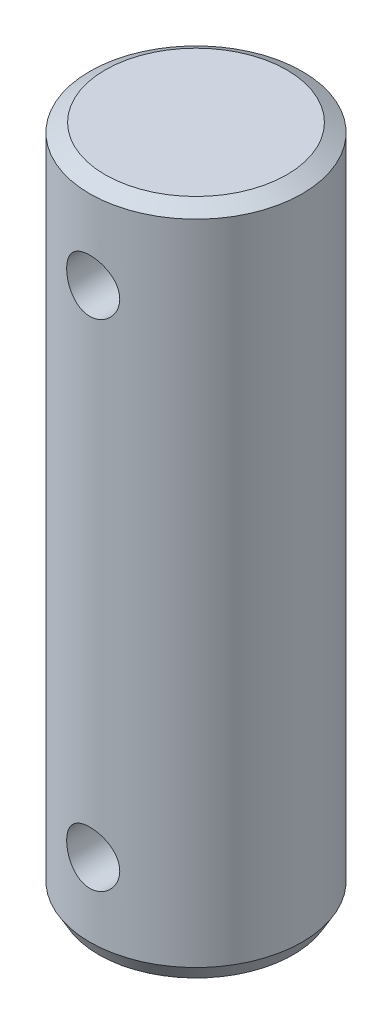
SolidWorks part; units mm, degrees
ref_plane "Front Plane" through (0, 0, 0) normal (0, 0, 1) x (1, 0, 0)
ref_plane "Top Plane" through (0, 0, 0) normal (0, 1, 0) x (1, 0, 0)
ref_plane "Right Plane" through (0, 0, 0) normal (1, 0, 0) x (0, 0, -1)
sketch "Sketch1" plane through (0, 0, 0) normal (0, 1, 0) x (1, 0, 0)
  circle A0 centre (0, 0) radius 6
  dimension "D1" = 12
extrude "Boss-Extrude1" add sketch "Sketch1" along normal mid plane 38
chamfer "Chamfer1" distance 0.5 angle 60 2 edges at (0, -19, 6) (0, 19, 6)
sketch "Sketch2" plane through (0, 0, 0) normal (0, 0, 1) x (1, 0, 0)
  line L0 (5.134, 19) -> (-5.134, 19) construction
  line L1 (-5.5, -19) -> (5.5, -19) construction
  circle A0 centre (0, 14) radius 1.5
  circle A1 centre (0, -14) radius 1.5
  dimension "D1" = 3
  dimension "D2" = 3
  dimension "D3" = 5
  dimension "D4" = 5
extrude "Cut-Extrude1" cut sketch "Sketch2" against normal mid plane 38
